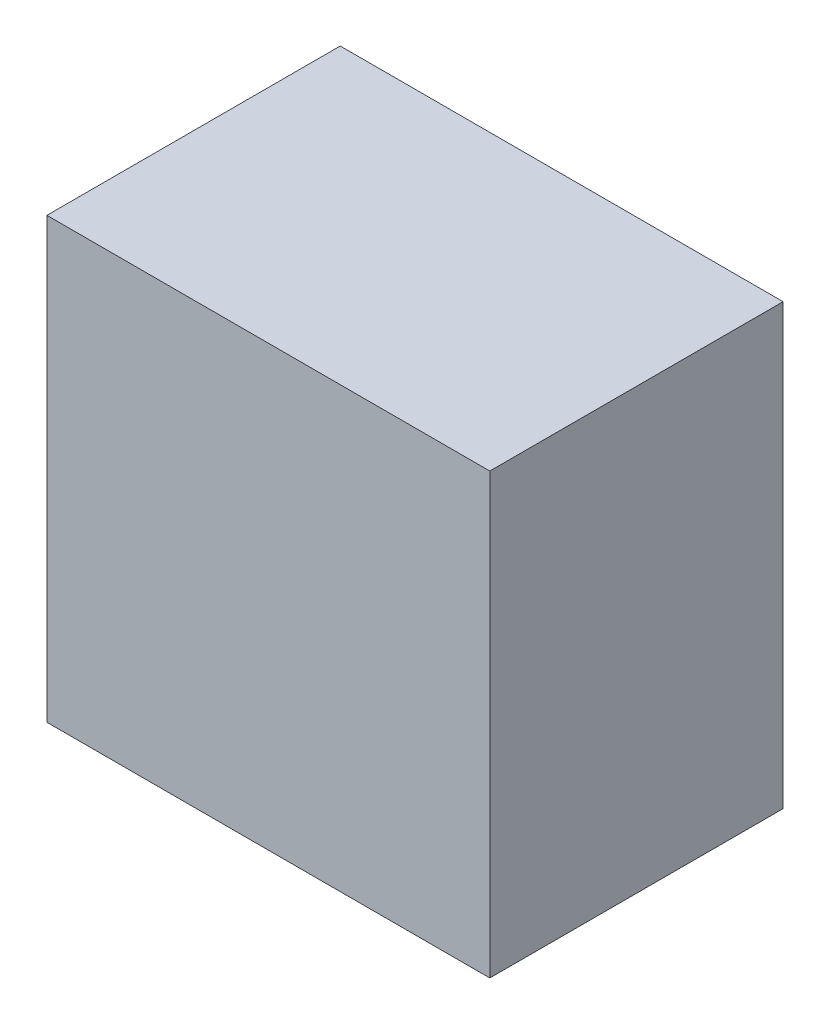
SolidWorks part; units mm, degrees
ref_plane "Front Plane" through (0, 0, 0) normal (0, 0, 1) x (1, 0, 0)
ref_plane "Top Plane" through (0, 0, 0) normal (0, 1, 0) x (1, 0, 0)
ref_plane "Right Plane" through (0, 0, 0) normal (1, 0, 0) x (0, 0, -1)
sketch "Sketch1" plane through (0, 0, 0) normal (0, 0, 1) x (1, 0, 0)
  line L0 (-0.76, 0.8) -> (0.75, 0.8)
  line L1 (0.75, 0.8) -> (0.75, -0.697)
  line L2 (0.75, -0.697) -> (-0.76, -0.697)
  line L3 (-0.76, -0.697) -> (-0.76, 0.8)
extrude "Component_Outline" add sketch "Sketch1" along normal blind 1 separate body
sketch3d "3DSketch1"
  line L0 (0, 0, 0) -> (1, 0, 0)
  line L1 (0, 0, 0) -> (0, 1, 0)
  line L2 (0, 0, 0) -> (0, 0, 1)
  point P0 (0, 0, 0)
